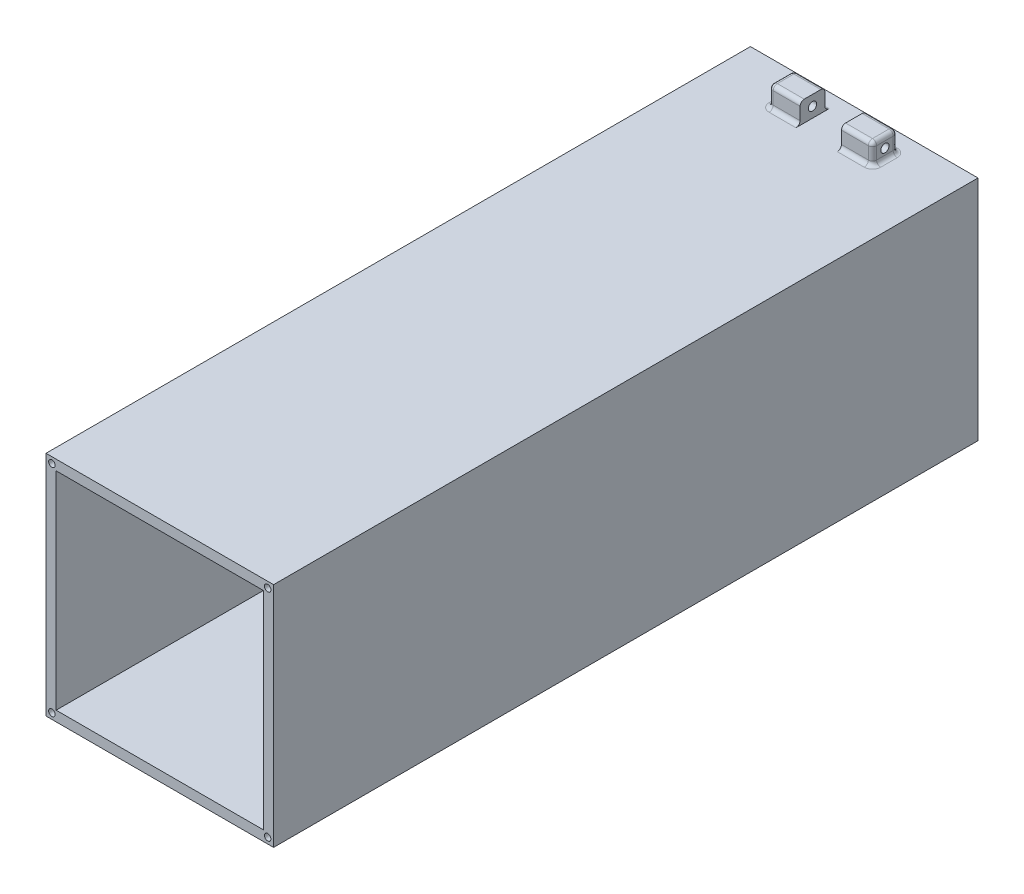
SolidWorks part; units mm, degrees
material "2024-T4"
ref_plane "Front Plane" through (0, 0, 0) normal (0, 0, 1) x (1, 0, 0)
ref_plane "Top Plane" through (0, 0, 0) normal (0, 1, 0) x (1, 0, 0)
ref_plane "Right Plane" through (0, 0, 0) normal (1, 0, 0) x (0, 0, -1)
sketch "Sketch1" plane through (0, 0, 0) normal (0, 0, 1) x (1, 0, 0)
  line L1 (55, -55) -> (-55, -55)
  line L2 (55, -55) -> (55, 55)
  line L3 (55, 55) -> (-55, 55)
  line L4 (-55, -55) -> (-55, 55)
  line L5 (55, -55) -> (-55, 55) construction
  line L6 (55, 55) -> (-55, -55) construction
  line L7 (50.1, -50.1) -> (-50.1, -50.1)
  line L8 (50.1, -50.1) -> (50.1, 50.1)
  line L9 (50.1, 50.1) -> (-50.1, 50.1)
  line L10 (-50.1, -50.1) -> (-50.1, 50.1)
  line L11 (50.1, -50.1) -> (-50.1, 50.1) construction
  line L12 (50.1, 50.1) -> (-50.1, -50.1) construction
  point P0 (0, 0)
  point P6 (0, 0)
  dimension "D1" = 110
  dimension "D2" = 110
  dimension "D3" = 4.9
extrude "Boss-Extrude1" add sketch "Sketch1" along normal blind 340.5 contours L4 L1 L2 L3 L7 L10 L9 L8
sketch "Sketch2" plane through (0, 0, 340.5) normal (0, 0, 1) x (1, 0, 0)
  line L0 (-50.1, 50.1) -> (-55, 55) construction
  line L1 (0, -60.5) -> (0, 60.5) construction
  line L2 (60.5, 0) -> (-60.5, 0) construction
  circle A0 centre (-52.1491, 52.1491) radius 1.575
  circle A1 centre (52.1491, 52.1491) radius 1.575
  circle A2 centre (52.1491, -52.1491) radius 1.575
  circle A3 centre (-52.1491, -52.1491) radius 1.575
  dimension "D1" = 3.15
  dimension "D2" = 73.75
extrude "Cut-Extrude1" cut sketch "Sketch2" against normal up to next
sketch "Sketch3" plane through (0, 0, 0) normal (1, 0, 0) x (0, 0, -1)
  line L1 (0, -55) -> (-10, -55)
  line L2 (0, -55) -> (0, -65)
  line L3 (0, -65) -> (-10, -65)
  line L4 (-10, -55) -> (-10, -65)
  dimension "D1" = 10
  dimension "D2" = 10
extrude "Boss-Extrude3" add sketch "Sketch3" along normal blind 30 and the other way blind 30
sketch "Sketch4" plane through (-30, 0, 0) normal (-1, 0, 0) x (0, 0, 1)
  line L0 (5, -60) -> (5, -55) construction
  line L1 (0, -55) -> (10, -55) construction
  line L2 (5, -60) -> (10, -60) construction
  line L3 (10, -55) -> (10, -65) construction
  circle A0 centre (5, -60) radius 1.5
  dimension "D1" = 3
extrude "Cut-Extrude2" cut sketch "Sketch4" against normal up to surface (60 mm away) up to face at (30, -60, 5)
sketch "Sketch5" plane through (-30, 0, 0) normal (-1, 0, 0) x (0, 0, 1)
  line L0 (0, -55) -> (5, -60) construction
  line L2 (5, -60) -> (5, -55) construction
  line L3 (0, -55) -> (10, -55) construction
sketch "Sketch6" plane through (0, 55, 0) normal (0, 1, 0) x (1, 0, 0)
  line L0 (-25, -15) -> (-55, -15) construction
  line L1 (-25, -9) -> (-10, -9)
  line L2 (-25, -9) -> (-25, -21)
  line L3 (-25, -21) -> (-10, -21)
  line L4 (-10, -9) -> (-10, -21)
  line L5 (10, -9) -> (25, -9)
  line L6 (10, -9) -> (10, -21)
  line L7 (10, -21) -> (25, -21)
  line L8 (25, -9) -> (25, -21)
  line L9 (-55, -340.5) -> (-55, 0) construction
  line L10 (25, -15) -> (55, -15) construction
  line L11 (55, -340.5) -> (55, 0) construction
  line L12 (-25, -15) -> (-25, 0) construction
  line L13 (55, 0) -> (-55, 0) construction
  dimension "D1" = 30
  dimension "D2" = 15
  dimension "D3" = 12
  dimension "D4" = 15
extrude "Boss-Extrude4" add sketch "Sketch6" along normal blind 10
sketch "Sketch7" plane through (-25, 0, 0) normal (-1, 0, 0) x (0, 0, 1)
  line L2 (15, 60) -> (21, 60) construction
  line L3 (21, 65) -> (21, 55) construction
  line L4 (15, 60) -> (9, 60) construction
  line L5 (9, 65) -> (9, 55) construction
  circle A0 centre (15, 60) radius 2
  dimension "D1" = 4
extrude "Cut-Extrude3" cut sketch "Sketch7" against normal up to surface (50 mm away) up to face at (25, 60, 15)
fillet "Fillet1" radius 2 16 edges at (17.5, 55, 21) (17.5, 55, 9) (-17.5, 55, 9) (-17.5, 55, 21) (17.5, 65, 9) (25, 60, 21) (25, 60, 9) (25, 55, 15) (25, 65, 15) (17.5, 65, 21) (-25, 60, 9) (-25, 65, 15) (-25, 55, 15) (-25, 60, 21) (-17.5, 65, 21) (-17.5, 65, 9)
fillet "Fillet2" radius 3 3 edges at (0, -55, 10) (0, -65, 10) (0, -65, 0)
